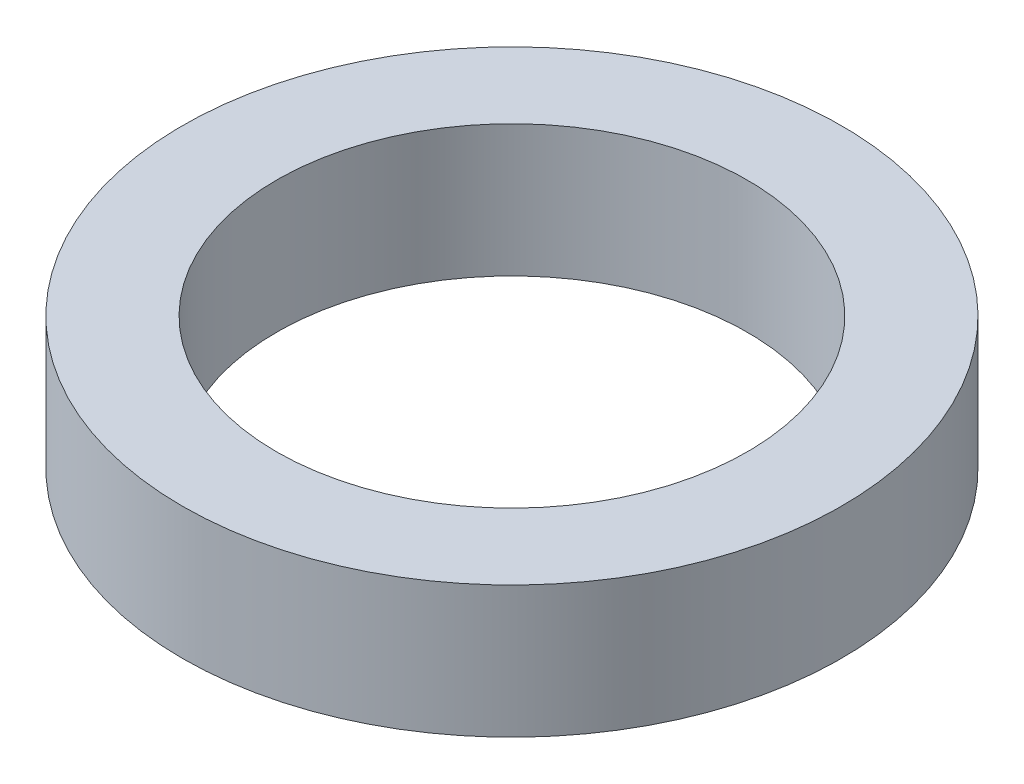
SolidWorks part; units mm, degrees
ref_plane "Front Plane" through (0, 0, 0) normal (0, 0, 1) x (1, 0, 0)
ref_plane "Top Plane" through (0, 0, 0) normal (0, 1, 0) x (1, 0, 0)
ref_plane "Right Plane" through (0, 0, 0) normal (1, 0, 0) x (0, 0, -1)
sketch "Sketch1" plane through (0, 0, 0) normal (0, 1, 0) x (1, 0, 0)
  circle A0 centre (0, 0) radius 35
  circle A1 centre (0, 0) radius 25
  dimension "D1" = 70
  dimension "D2" = 50
extrude "Boss-Extrude1" add sketch "Sketch1" along normal blind 14
